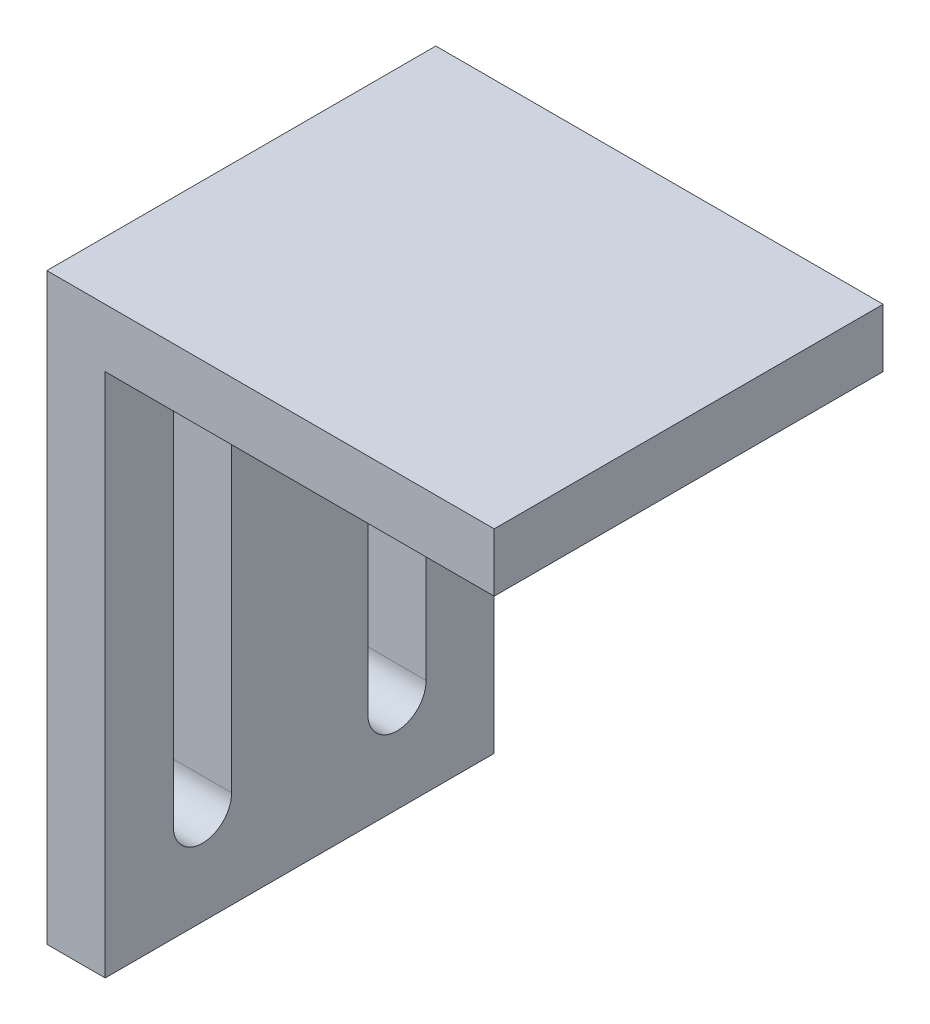
SolidWorks part; units mm, degrees
ref_plane "Front Plane" through (0, 0, 0) normal (0, 0, 1) x (1, 0, 0)
ref_plane "Top Plane" through (0, 0, 0) normal (0, 1, 0) x (1, 0, 0)
ref_plane "Right Plane" through (0, 0, 0) normal (1, 0, 0) x (0, 0, -1)
sketch "Sketch1" plane through (0, 0, 0) normal (1, 0, 0) x (0, 0, -1)
  line L0 (-5, 10) -> (-5, -10) construction
  line L1 (-10, 15) -> (10, 15)
  line L2 (-10, 15) -> (-10, -15)
  line L3 (-10, -15) -> (10, -15)
  line L4 (10, 15) -> (10, -15)
  line L5 (-10, 15) -> (10, -15) construction
  line L6 (-10, -15) -> (10, 15) construction
  line L7 (-3.5, 10) -> (-3.5, -10)
  line L8 (-6.5, 10) -> (-6.5, -10)
  line L9 (5, 10) -> (5, -10) construction
  line L10 (6.5, 10) -> (6.5, -10)
  line L11 (3.5, 10) -> (3.5, -10)
  arc A0 (-3.5, 10) -> (-6.5, 10) centre (-5, 10) ccw
  arc A1 (-6.5, -10) -> (-3.5, -10) centre (-5, -10) ccw
  arc A2 (6.5, 10) -> (3.5, 10) centre (5, 10) ccw
  arc A3 (3.5, -10) -> (6.5, -10) centre (5, -10) ccw
  point P0 (0, 0)
  point P8 (-5, 0)
  point P17 (5, 0)
  dimension "D5" = 1.5
  dimension "D1" = 20
  dimension "D2" = 30
  dimension "D3" = 20
  dimension "D4" = 5
  dimension "D6" = 5
  dimension "D7" = 2
extrude "Boss-Extrude1" add sketch "Sketch1" along normal blind 3
sketch "Sketch2" plane through (3, 0, 0) normal (1, 0, 0) x (0, 0, -1)
  line L0 (10, -15) -> (10, 15) construction
  line L1 (-10, 15) -> (10, 15)
  line L2 (-10, 15) -> (-10, 12)
  line L3 (-10, 12) -> (10, 12)
  line L4 (10, 15) -> (10, 12)
  dimension "D1" = 3
extrude "Boss-Extrude2" add sketch "Sketch2" along normal blind 20
